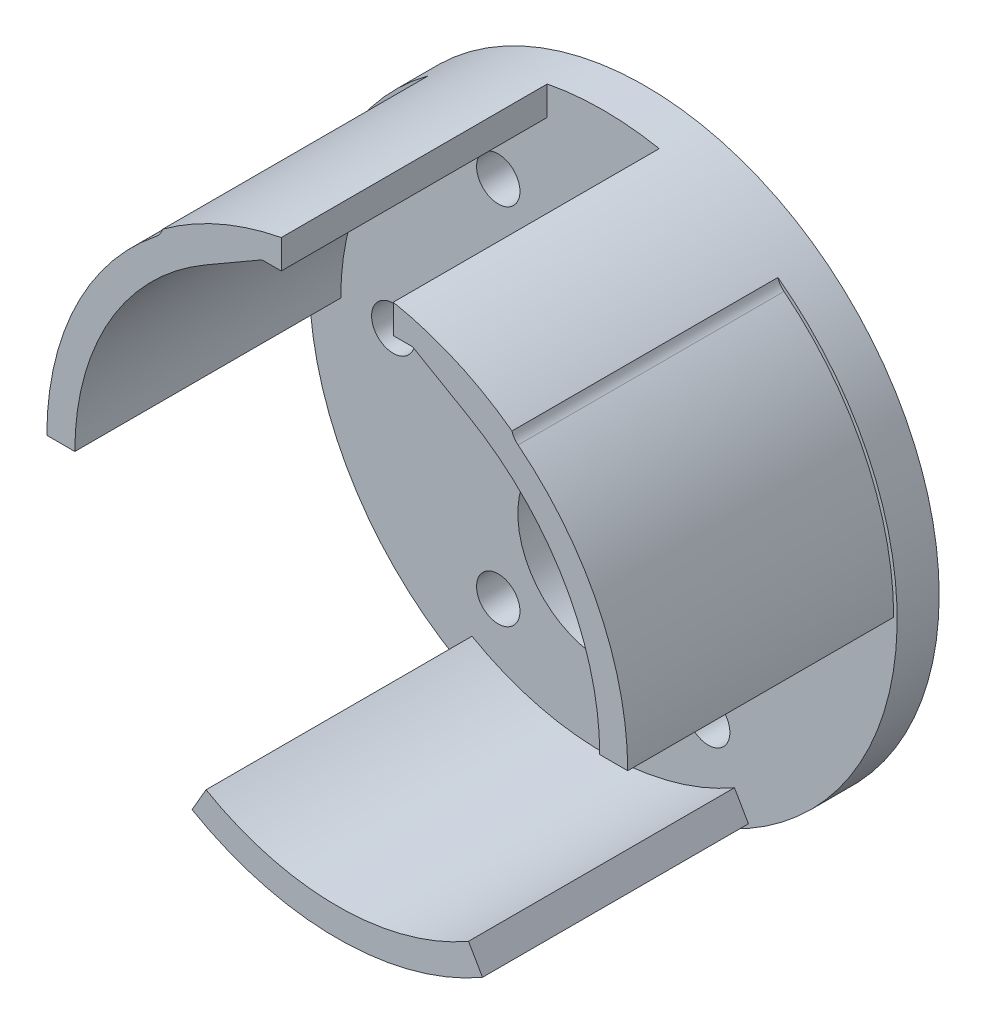
SolidWorks part; units mm, degrees
ref_plane "Front Plane" through (0, 0, 0) normal (0, 0, 1) x (1, 0, 0)
ref_plane "Top Plane" through (0, 0, 0) normal (0, 1, 0) x (1, 0, 0)
ref_plane "Right Plane" through (0, 0, 0) normal (1, 0, 0) x (0, 0, -1)
sketch "Sketch1" plane through (0, 0, 0) normal (0, 0, 1) x (1, 0, 0)
  line L0 (0, 25) -> (0, 0) construction
  line L1 (0, 1.4545) -> (-18.5, 1.4545) construction
  line L2 (-7.5, 14.4449) -> (0, 1.4545) construction
  line L3 (-7.5, -11.5359) -> (0, 1.4545) construction
  line L4 (-45, 0) -> (0, 0) construction
  line L5 (-46.6249, -4.7286) -> (-6.8247, -18.4056) construction
  line L6 (-48.4169, 3.6504) -> (-11.959, 37.7762)
  line L7 (46.6249, -4.7286) -> (6.8247, -18.4056) construction
  line L8 (48.4169, 3.6504) -> (11.959, 37.7762)
  line L9 (-16, -19.5455) -> (16, -19.5455)
  line L10 (-17.6678, -19.1542) -> (-47.2237, -4.4783)
  line L11 (17.6678, -19.1542) -> (47.2237, -4.4783)
  circle A0 centre (-25, 0) radius 2.5
  circle A1 centre (0, 1.4545) radius 18.5 construction
  circle A2 centre (0, -5.5455) radius 6.1
  circle A3 centre (0, 1.4545) radius 15 construction
  circle A4 centre (-7.5, 14.4449) radius 1.55
  circle A5 centre (-15, 1.4545) radius 1.55
  circle A6 centre (-7.5, -11.5359) radius 1.55
  circle A7 centre (-45, 0) radius 5 construction
  circle A8 centre (0, 25) radius 17.5 construction
  circle A9 centre (0, 1.4545) radius 21 construction
  arc A10 (-48.4169, 3.6504) -> (-46.6249, -4.7286) centre (-45, 0) ccw construction
  circle A11 centre (7.5, -11.5359) radius 1.55
  circle A12 centre (7.5, 14.4449) radius 1.55
  circle A13 centre (15, 1.4545) radius 1.55
  circle A14 centre (25, 0) radius 2.5
  arc A15 (48.4169, 3.6504) -> (46.6249, -4.7286) centre (45, 0) cw construction
  arc A16 (-11.959, 37.7762) -> (11.959, 37.7762) centre (0, 25) cw
  arc A17 (6.8247, -18.4056) -> (-6.8247, -18.4056) centre (0, 1.4545) cw construction
  circle A18 centre (-45, 0) radius 2.5
  circle A19 centre (45, 0) radius 2.5
  circle A20 centre (-16, -15.7955) radius 3.75 construction
  circle A21 centre (-16, -15.7955) radius 2.5
  arc A22 (-48.4169, 3.6504) -> (-47.2237, -4.4783) centre (-45, 0) ccw
  arc A23 (-17.6678, -19.1542) -> (-16, -19.5455) centre (-16, -15.7955) ccw
  circle A24 centre (16, -15.7955) radius 3.75 construction
  circle A25 centre (16, -15.7955) radius 2.5
  arc A26 (17.6678, -19.1542) -> (16, -19.5455) centre (16, -15.7955) cw
  arc A27 (48.4169, 3.6504) -> (47.2237, -4.4783) centre (45, 0) cw
  point P53 (0, -19.5455)
  dimension "D1" = 5
  dimension "D2" = 50
  dimension "D3" = 37
  dimension "D5" = 12.2
  dimension "D9" = 3.1
  dimension "D10" = 30
  dimension "D12" = 10
  dimension "D13" = 35
  dimension "D15" = 42
  dimension "D16" = 5
  dimension "D17" = 7.5
  dimension "D18" = 5
  dimension "D4" = 1.4545
  dimension "D6" = 7
  dimension "D7" = 60
  dimension "D8" = 60
  dimension "D11" = 45
  dimension "D14" = 25
  dimension "D19" = 16
extrude "Boss-Extrude1" add sketch "Sketch1" along normal blind 3
sketch "Sketch2" plane through (0, 0, 3) normal (0, 0, 1) x (1, 0, 0)
  line L0 (0, 0) -> (0, 22.2045) construction
  line L1 (0, 1.4545) -> (-10.375, -16.5155) construction
  line L2 (0, 1.4545) -> (10.375, -16.5155) construction
  line L3 (0, 1.4545) -> (-20.75, 1.4545) construction
  line L4 (0, 1.4545) -> (-10.375, 19.4245) construction
  line L5 (-10.375, 19.4245) -> (-9.375, 17.6925)
  line L6 (-20.75, 1.4545) -> (-18.75, 1.4545)
  line L7 (-10.375, -16.5155) -> (-9.375, -14.7835)
  line L8 (10.375, -16.5155) -> (9.375, -14.7835)
  line L9 (10.375, 19.4245) -> (9.375, 17.6925)
  line L10 (20.75, 1.4545) -> (18.75, 1.4545)
  circle A0 centre (0, 1.4545) radius 18.5 construction
  circle A1 centre (0, 1.4545) radius 18.5 construction
  circle A2 centre (0, 1.4545) radius 18.75 construction
  circle A3 centre (0, 1.4545) radius 20.75 construction
  arc A4 (-20.75, 1.4545) -> (-10.375, 19.4245) centre (0, 1.4545) cw
  arc A5 (-18.75, 1.4545) -> (-9.375, 17.6925) centre (0, 1.4545) cw
  arc A6 (-9.375, -14.7835) -> (9.375, -14.7835) centre (0, 1.4545) ccw
  arc A7 (-10.375, -16.5155) -> (10.375, -16.5155) centre (0, 1.4545) ccw
  arc A8 (20.75, 1.4545) -> (10.375, 19.4245) centre (0, 1.4545) ccw
  arc A9 (18.75, 1.4545) -> (9.375, 17.6925) centre (0, 1.4545) ccw
  dimension "D1" = 37.5
  dimension "D2" = 2
  dimension "D3" = 150
  dimension "D4" = 150
  dimension "D5" = 60
  dimension "D6" = 60
extrude "Boss-Extrude2" add sketch "Sketch2" along normal blind 39 contours L6 A5 L5 A4 | L7 A7 L8 A6 | A9 L10 A8 L9
sketch "Sketch3" plane through (0, 0, 3) normal (0, 0, 1) x (1, 0, 0)
  line L0 (0, 0) -> (0, 23) construction
  line L1 (-12.5, 38) -> (12.5, 38) construction
  line L2 (-12.5, 38) -> (-12.5, 23) construction
  line L3 (-12.5, 23) -> (12.5, 23) construction
  line L4 (12.5, 38) -> (12.5, 23) construction
  line L5 (0, 25) -> (0, 0) construction
  line L6 (-17.5, 29) -> (-17.5, 23)
  line L7 (-17.5, 23) -> (-4, 23)
  line L8 (-4, 23) -> (-4, 20)
  line L9 (-4, 20) -> (-5.3783, 20)
  line L10 (-17.5, 29) -> (-20.5, 29)
  line L11 (-20.5, 29) -> (-20.5, 20)
  line L12 (-20.5, 20) -> (-13.7246, 20)
  line L13 (-9.375, 17.6925) -> (-5.3783, 20)
  line L14 (-12.9186, 17.6925) -> (-9.375, 17.6925)
  arc A0 (-9.375, 17.6925) -> (-18.75, 1.4545) centre (0, 1.4545) ccw construction
  arc A1 (-13.7246, 20) -> (-12.9186, 17.6925) centre (-13.7246, 18.7055) cw
  arc A2 (-10.375, 19.4245) -> (-20.75, 1.4545) centre (0, 1.4545) ccw construction
  dimension "D1" = 25
  dimension "D2" = 15
  dimension "D3" = 23
  dimension "D4" = 8
  dimension "D5" = 3
  dimension "D6" = 35
  dimension "D7" = 3
  dimension "D8" = 6
extrude "Boss-Extrude3" add sketch "Sketch3" along normal up to surface (39 mm away) up to face at (-15.9583, 10.668, 42)
mirror "Mirror1" about plane through (0, 0, 0) normal (1, 0, 0) of "Boss-Extrude3"
sketch "Sketch4" plane through (0, 23, 0) normal (0, 1, 0) x (1, 0, 0)
  line L0 (-13.7246, -42) -> (-13.7246, -3) construction
  line L1 (-13.7246, -42) -> (-13.7246, -3) construction
  line L2 (-15.7246, -17.5) -> (-15.7246, -27.5) construction
  line L3 (-14.2246, -17.5) -> (-14.2246, -27.5)
  line L4 (-17.2246, -17.5) -> (-17.2246, -27.5)
  line L5 (-15.7246, -22.5) -> (-13.7246, -22.5) construction
  line L6 (0, 0) -> (0, -40.251) construction
  line L7 (15.7246, -17.5) -> (15.7246, -27.5) construction
  line L8 (14.2246, -17.5) -> (14.2246, -27.5)
  line L9 (17.2246, -17.5) -> (17.2246, -27.5)
  arc A0 (-14.2246, -17.5) -> (-17.2246, -17.5) centre (-15.7246, -17.5) ccw
  arc A1 (-17.2246, -27.5) -> (-14.2246, -27.5) centre (-15.7246, -27.5) ccw
  arc A2 (14.2246, -17.5) -> (17.2246, -17.5) centre (15.7246, -17.5) cw
  arc A3 (17.2246, -27.5) -> (14.2246, -27.5) centre (15.7246, -27.5) cw
  point P4 (-15.7246, -22.5)
  point P16 (15.7246, -22.5)
  dimension "D1" = 3
  dimension "D2" = 2
  dimension "D3" = 10
extrude "Cut-Extrude1" cut sketch "Sketch4" against normal up to surface (3 mm away) up to face at (-17.1123, 20, 22.5)
sketch "Sketch5" plane through (0, 0, 3) normal (0, 0, 1) x (1, 0, 0)
  line L0 (-43.7844, 23.3468) -> (-43.7844, 6.0404)
  line L1 (-43.7844, 6.0404) -> (-29.1766, -7.7395)
  line L2 (-27.9848, -4.7395) -> (-40.7844, 7.3346)
  line L3 (-40.7844, 7.3346) -> (-40.7844, 23.3468)
  line L4 (-43.7844, 23.3468) -> (-40.7844, 23.3468)
  line L6 (-27.9848, -4.7395) -> (-18.0861, -4.7395)
  line L7 (-29.1766, -7.7395) -> (-18.0861, -7.7395)
  line L8 (-18.0861, -7.7395) -> (-18.0861, -4.7395)
  dimension "D1" = 3
  dimension "D2" = 3
  dimension "D3" = 3
extrude "Boss-Extrude4" add sketch "Sketch5" along normal blind 34
mirror "Mirror2" about plane through (0, 0, 0) normal (1, 0, 0) of "Boss-Extrude4"
sketch "Sketch6" plane through (0, 0, 3) normal (0, 0, -1) x (-1, 0, 0)
  line L4 (40.7844, 23.3468) -> (40.7844, 10.7946)
  line L5 (40.7844, 10.7946) -> (43.7844, 7.9865)
  line L6 (43.7844, 7.9865) -> (43.7844, 23.3468)
  line L7 (43.7844, 23.3468) -> (40.7844, 23.3468)
  line L8 (40.7844, 23.3468) -> (40.7844, 10.7946)
  line L9 (40.7844, 10.7946) -> (43.7844, 7.9865)
  line L10 (43.7844, 7.9865) -> (43.7844, 23.3468)
  line L11 (43.7844, 23.3468) -> (40.7844, 23.3468)
  line L12 (-43.7844, 23.3468) -> (-43.7844, 7.9865)
  line L13 (-43.7844, 7.9865) -> (-40.7844, 10.7946)
  line L14 (-40.7844, 10.7946) -> (-40.7844, 23.3468)
  line L15 (-40.7844, 23.3468) -> (-43.7844, 23.3468)
  line L16 (-43.7844, 23.3468) -> (-43.7844, 7.9865)
  line L17 (-43.7844, 7.9865) -> (-40.7844, 10.7946)
  line L18 (-40.7844, 10.7946) -> (-40.7844, 23.3468)
  line L19 (-40.7844, 23.3468) -> (-43.7844, 23.3468)
  dimension "D1" = 0
  dimension "D2" = 0
extrude "Boss-Extrude5" add sketch "Sketch6" along normal up to surface (3 mm away) up to face at (0, 0.0404, 0)
sketch "Sketch7" plane through (0, 0, 3) normal (0, 0, 1) x (1, 0, 0)
  circle A0 centre (-18.7282, -11.5671) radius 3.75 construction
  circle A1 centre (-18.7282, -11.5671) radius 2.5
  dimension "D1" = 7.5
  dimension "D2" = 5
sketch "Sketch8" plane through (0, 0, 3) normal (0, 0, 1) x (1, 0, 0)
  line L1 (-51.7865, 53.5853) -> (50.6856, 53.5853)
  line L2 (-51.7865, 53.5853) -> (-51.7865, -24.7012)
  line L3 (-51.7865, -24.7012) -> (50.6856, -24.7012)
  line L4 (50.6856, 53.5853) -> (50.6856, -24.7012)
  line L5 (50.6856, -1.9689) -> (-24.865, -1.9689)
  line L6 (50.6856, -1.9689) -> (50.6856, -10.9708)
  line L7 (50.6856, -10.9708) -> (-24.865, -10.9708)
  line L8 (-24.865, -1.9689) -> (-24.865, -10.9708)
  circle A0 centre (0, 1.4545) radius 21 construction
  circle A1 centre (0, 1.4545) radius 21
  point P11 (34.6867, -23.7172)
  point P12 (-24.865, -10.9708)
  point P13 (50.6856, -24.7012)
extrude "Cut-Extrude3" cut sketch "Sketch8" along normal through all contours A1 L7 L8 L5 L4 L1 L2 L3 | L5 A1 L7 | A1 L5 L8 L7 | A1 L7 L4 L5
sketch "Sketch9" plane through (0, 0, 3) normal (0, 0, 1) x (1, 0, 0)
  line L1 (-60.1211, 49.2614) -> (55.6206, 49.2614)
  line L2 (-60.1211, 49.2614) -> (-60.1211, -27.4703)
  line L3 (-60.1211, -27.4703) -> (55.6206, -27.4703)
  line L4 (55.6206, 49.2614) -> (55.6206, -27.4703)
  circle A0 centre (0, 1.4545) radius 21 construction
  circle A1 centre (0, 1.4545) radius 21
extrude "Cut-Extrude4" cut sketch "Sketch9" against normal blind 10
sketch "Sketch10" plane through (0, 0, 42) normal (0, 0, 1) x (1, 0, 0)
  line L1 (-27.9699, 25.8015) -> (24.4945, 25.8015)
  line L2 (-27.9699, 25.8015) -> (-27.9699, -25.8634)
  line L3 (-27.9699, -25.8634) -> (24.4945, -25.8634)
  line L4 (24.4945, 25.8015) -> (24.4945, -25.8634)
extrude "Cut-Extrude5" cut sketch "Sketch10" against normal blind 20
equation "\"D4@Sketch2\"=\"D3@Sketch2\""
